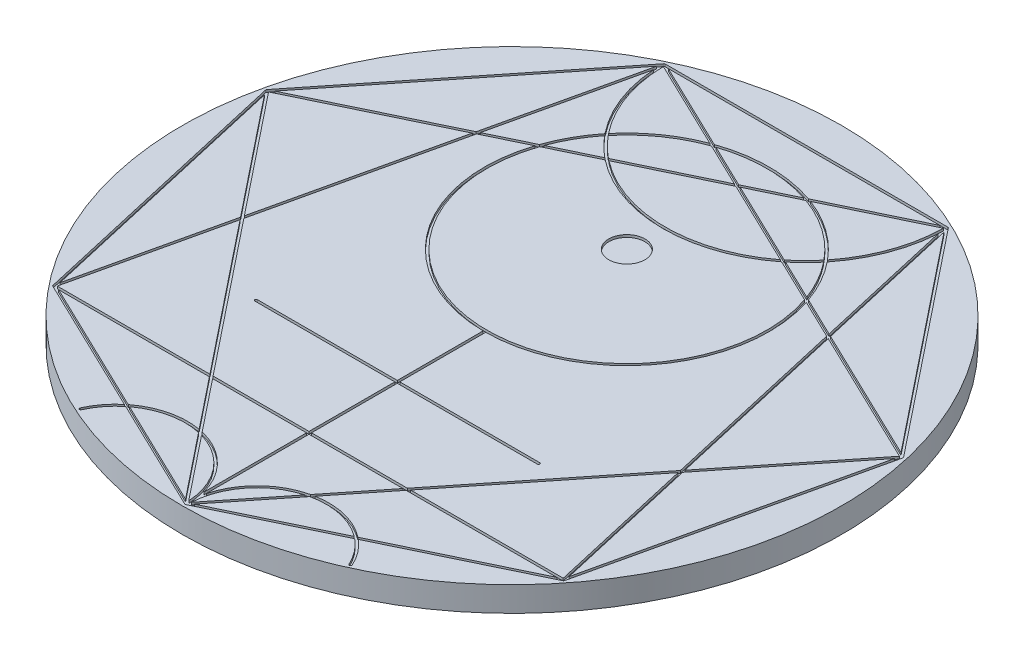
SolidWorks part; units mm, degrees
ref_plane "Front Plane" through (0, 0, 0) normal (0, 0, 1) x (1, 0, 0)
ref_plane "Top Plane" through (0, 0, 0) normal (0, 1, 0) x (1, 0, 0)
ref_plane "Right Plane" through (0, 0, 0) normal (1, 0, 0) x (0, 0, -1)
sketch "Sketch1" plane through (0, 0, 0) normal (0, 1, 0) x (1, 0, 0)
  circle A0 centre (0, 0) radius 132.5
  dimension "D1" = 265
extrude "Boss-Extrude1" add sketch "Sketch1" against normal blind 10
sketch "Sketch2" plane through (0, 0, 0) normal (0, 1, 0) x (1, 0, 0)
  line L0 (-102.3417, -81.6148) -> (102.3417, -81.6148)
  line L1 (102.3417, -81.6148) -> (56.7954, 117.9368)
  line L2 (56.7954, 117.9368) -> (-127.6181, 29.128)
  line L3 (-127.6181, 29.128) -> (0, -130.9)
  line L4 (0, -130.9) -> (127.6181, 29.128)
  line L5 (127.6181, 29.128) -> (-56.7954, 117.9368)
  line L6 (-56.7954, 117.9368) -> (-102.3417, -81.6148)
  line L7 (56.7954, 117.9368) -> (56.7954, 63.2344) construction
  line L8 (0, -130.9) -> (102.3417, -81.6148)
  line L9 (102.3417, -81.6148) -> (127.6181, 29.128)
  line L10 (127.6181, 29.128) -> (56.7954, 117.9368)
  line L11 (56.7954, 117.9368) -> (-56.7954, 117.9368)
  line L12 (-56.7954, 117.9368) -> (-127.6181, 29.128)
  line L13 (-127.6181, 29.128) -> (-102.3417, -81.6148)
  line L14 (-102.3417, -81.6148) -> (0, -130.9)
  line L15 (-56.7954, 117.9368) -> (-56.7954, 63.2344) construction
  line L16 (-56.7954, 90.5856) -> (56.7954, 90.5856) construction
  line L17 (-56.7954, 63.2344) -> (-56.7954, -119.7102) construction
  line L18 (0, -130.9) -> (0, -10.6142)
  line L19 (-35.4113, 73.5324) -> (-35.4113, 107.6388) construction
  line L20 (56.7954, -119.7102) -> (56.7954, 46.1812) construction
  line L21 (-56.7954, -46.1145) -> (56.7954, -46.1145)
  line L22 (56.7954, -10.6142) -> (-56.7954, -10.6142) construction
  line L23 (56.7954, -10.6142) -> (-56.7954, -81.6148) construction
  line L24 (0, -81.6148) -> (-56.7954, -46.1145) construction
  line L25 (56.7954, -81.6148) -> (-56.7954, -10.6142) construction
  line L26 (0, -81.6148) -> (56.7954, -46.1145) construction
  line L27 (56.7954, -46.1145) -> (0, -10.6142) construction
  line L28 (0, -10.6142) -> (-56.7954, -46.1145) construction
  line L29 (35.4113, 107.6388) -> (35.4113, 73.5324) construction
  circle A0 centre (0, 0) radius 130.9
  circle A1 centre (0, 0) radius 117.9368 construction
  circle A3 centre (0, 46.1812) radius 56.7954
  arc A4 (-0.0451, -132.5) -> (-54.8645, -120.6074) centre (-28.3977, -130.9) ccw
  arc A5 (54.8645, -120.6074) -> (0.0451, -132.5) centre (28.3977, -130.9) ccw
  circle A6 centre (0, 0) radius 132.5
  circle A7 centre (0, 0) radius 132.5 construction
  circle A9 centre (0, 46.1812) radius 7.27
  arc A10 (-56.7673, 119.7235) -> (56.7673, 119.7235) centre (0, 117.9368) ccw
  point P7 (35.4113, 90.5856)
  point P31 (0, -130.9)
  point P33 (-35.4113, 90.5856)
  point P40 (0, -46.1145)
  point P50 (-28.3977, -63.8647)
  point P54 (28.3977, -28.3643)
  point P55 (28.3977, -63.8647)
  point P56 (-28.3977, -28.3643)
  point P57 (-35.4113, 90.5856)
  point P58 (0, 0)
  point P59 (0, 0)
  point P60 (35.4113, 90.5856)
  dimension "D1" = 261.8
  dimension "D2" = 14.54
sketch "Sketch4" plane through (0, 0, 0) normal (0, 1, 0) x (1, 0, 0)
  line L4 (0, -130.9) -> (0, -10.6142) construction
  line L11 (-0.5, -123.3637) -> (-0.5, -46.6145)
  line L12 (0.5, -123.3637) -> (0.5, -46.6145)
  line L13 (56.7954, -46.1145) -> (-56.7954, -46.1145) construction
  line L14 (56.7954, -46.6145) -> (0.5, -46.6145)
  line L15 (56.7954, -45.6145) -> (0.5, -45.6145)
  line L16 (-0.5, -46.6145) -> (-56.7954, -46.6145)
  line L17 (-0.5, -45.6145) -> (-0.5, -11.112)
  line L18 (-0.5, -45.6145) -> (-56.7954, -45.6145)
  line L19 (0.5, -45.6145) -> (0.5, -11.112)
  circle A11 centre (0, 46.1812) radius 7.27
  circle A42 centre (0, 0) radius 130.9 construction
  arc A43 (54.8645, -120.6074) -> (0.0451, -132.5) centre (28.3977, -130.9) ccw construction
  arc A44 (54.2425, -119.1325) -> (0, -130.9) centre (28.3977, -130.9) ccw construction
  arc A45 (54.6976, -118.9253) -> (0.5, -123.3637) centre (28.3977, -130.9) ccw
  arc A46 (53.7875, -119.3397) -> (0.5, -130.9) centre (28.3977, -130.9) ccw
  arc A47 (53.7875, -119.3397) -> (54.6976, -118.9253) centre (54.2425, -119.1325) ccw
  arc A48 (-0.5, -130.9) -> (0.5, -130.9) centre (0, -130.9) ccw
  arc A49 (-0.5, -130.9) -> (0.5, -130.9) centre (0, -130.9) ccw
  arc A51 (56.7954, -46.6145) -> (56.7954, -45.6145) centre (56.7954, -46.1145) ccw
  arc A52 (-56.7954, -45.6145) -> (-56.7954, -46.6145) centre (-56.7954, -46.1145) ccw
  arc A53 (-54.2425, -119.1325) -> (0, -130.9) centre (-28.3977, -130.9) cw construction
  arc A54 (-53.7875, -119.3397) -> (-54.6976, -118.9253) centre (-54.2425, -119.1325) cw
  arc A55 (-54.6976, -118.9253) -> (-0.5, -123.3637) centre (-28.3977, -130.9) cw
  arc A56 (-53.7875, -119.3397) -> (-0.5, -130.9) centre (-28.3977, -130.9) cw
  arc A57 (-44.0241, 81.2675) -> (44.0241, 81.2675) centre (0, 46.1812) ccw
  arc A58 (0.5, -11.112) -> (44.6715, 82.059) centre (0, 46.1812) ccw
  arc A59 (56.7954, 117.9368) -> (-56.7954, 117.9368) centre (0, 117.9368) cw construction
  arc A60 (-57.2954, 117.9368) -> (-44.6715, 82.059) centre (0, 117.9368) ccw
  arc A61 (-56.2954, 117.9368) -> (-44.0241, 82.8505) centre (0, 117.9368) ccw
  arc A62 (-56.2954, 117.9368) -> (-57.2954, 117.9368) centre (-56.7954, 117.9368) ccw
  arc A63 (57.2954, 117.9368) -> (56.2954, 117.9368) centre (56.7954, 117.9368) ccw
  arc A64 (-56.7673, 119.7235) -> (56.7673, 119.7235) centre (0, 117.9368) ccw construction
  arc A65 (-44.0241, 81.2675) -> (44.0241, 81.2675) centre (0, 117.9368) ccw
  arc A66 (-44.6715, 82.059) -> (-0.5, -11.112) centre (0, 46.1812) ccw
  arc A67 (-43.3815, 82.059) -> (43.3815, 82.059) centre (0, 117.9368) ccw
  arc A68 (44.6715, 82.059) -> (57.2954, 117.9368) centre (0, 117.9368) ccw
  arc A69 (44.0241, 82.8505) -> (-44.0241, 82.8505) centre (0, 46.1812) ccw
  arc A70 (44.0241, 82.8505) -> (56.2954, 117.9368) centre (0, 117.9368) ccw
  arc A71 (43.3815, 82.059) -> (-43.3815, 82.059) centre (0, 46.1812) ccw
  circle A72 centre (0, 0) radius 132.5
  circle A73 centre (0, 46.1812) radius 56.2954
  point P0 (54.2425, -119.1325)
  point P1 (22.3771, -103.1479)
  point P16 (0, -70.7571)
  point P21 (0, -46.1145)
  point P42 (0, 61.1414)
  dimension "D1" = 1
  dimension "D2" = 1
  dimension "D3" = 1
  dimension "D4" = 1
  dimension "D5" = 1
  dimension "D6" = 14.54
extrude "Cut-Extrude2" cut sketch "Sketch4" against normal blind 1 contours A65 A73 A67 | A70 A69 A61 A62 A60 A66 L17 L18 A52 L16 L11 A55 A54 A56 A48 A46 A47 A45 L12 L14 A51 L15 L19 A58 A68 A63 A73 A57 A71 | A11
sketch "Sketch5" plane through (0, 0, 0) normal (0, 1, 0) x (1, 0, 0)
  line L0 (-102.3417, -81.6148) -> (102.3417, -81.6148) construction
  line L1 (0.2169, -131.3505) -> (102.5587, -82.0653)
  line L2 (102.8292, -81.7261) -> (128.1055, 29.0167)
  line L3 (128.009, 29.4397) -> (57.1863, 118.2486)
  line L4 (56.7954, 118.4368) -> (-56.7954, 118.4368)
  line L5 (-57.1863, 118.2486) -> (-128.009, 29.4397)
  line L6 (-128.1055, 29.0167) -> (-102.8292, -81.7261)
  line L7 (-102.5587, -82.0653) -> (-0.2169, -131.3505)
  line L9 (102.3417, -79.3678) -> (126.6431, 27.1035)
  line L10 (125.8613, 30.529) -> (57.7703, 115.9124)
  line L11 (54.6047, 117.4368) -> (-54.6047, 117.4368)
  line L15 (-101.7148, -81.1148) -> (-40.3419, -81.1148)
  line L16 (-100.1511, -82.1148) -> (-39.5444, -82.1148)
  line L17 (102.3417, -81.6148) -> (56.7954, 117.9368) construction
  line L19 (102.3417, -79.3678) -> (88.8555, -20.2807)
  line L20 (56.7954, 117.9368) -> (-127.6181, 29.128) construction
  line L22 (54.6047, 117.4368) -> (0, 91.1406)
  line L23 (-127.6181, 29.128) -> (0, -130.9) construction
  line L25 (-126.6431, 27.1035) -> (-88.8555, -20.2807)
  line L26 (0, -130.9) -> (127.6181, 29.128) construction
  line L28 (1.7568, -129.499) -> (39.5444, -82.1148)
  line L29 (127.6181, 29.128) -> (-56.7954, 117.9368) construction
  line L31 (125.8613, 30.529) -> (71.2566, 56.8252)
  line L32 (-102.3417, -81.6148) -> (-56.7954, 117.9368) construction
  line L33 (-102.3417, -79.3678) -> (-88.8555, -20.2807)
  line L36 (-57.7703, 115.9124) -> (-125.8613, 30.529)
  line L37 (-56.7047, 117.2486) -> (-57.0518, 116.8133) [skipped]
  line L38 (56.4474, 117.2143) -> (1.1524, 90.5856)
  line L39 (126.8362, 28.9495) -> (71.5412, 55.5782)
  line L40 (1.7568, -129.499) -> (100.1511, -82.1148)
  line L41 (101.7148, -81.1148) -> (88.058, -21.2807)
  line L42 (0.2169, -130.2406) -> (0.7185, -129.999) [skipped]
  line L43 (0, -130.0981) -> (38.2654, -82.1148)
  line L44 (-101.7148, -81.1148) -> (-88.058, -21.2807)
  line L45 (-100.1511, -82.1148) -> (-1.7568, -129.499)
  line L46 (-101.6909, -81.3733) -> (-101.1894, -81.6148) [skipped]
  line L47 (-126.6431, 27.1035) -> (-102.3417, -79.3678)
  line L48 (-127.0234, 28.7698) -> (-126.8996, 28.227) [skipped]
  line L49 (-126.8362, 28.9495) -> (-88.5709, -19.0337)
  line L50 (88.8555, -20.2807) -> (126.6431, 27.1035)
  line L51 (87.7734, -20.0337) -> (70.3888, 56.1332)
  line L52 (88.5709, -19.0337) -> (126.8362, 28.9495)
  line L53 (88.5709, -19.0337) -> (71.5412, 55.5782)
  line L54 (40.3419, -81.1148) -> (88.058, -21.2807)
  line L55 (39.5444, -82.1148) -> (100.1511, -82.1148)
  line L56 (39.0628, -81.1148) -> (87.7734, -20.0337)
  line L57 (40.3419, -81.1148) -> (101.7148, -81.1148)
  line L58 (-38.2654, -82.1148) -> (38.2654, -82.1148)
  line L59 (-39.5444, -82.1148) -> (-1.7568, -129.499)
  line L60 (-39.0628, -81.1148) -> (39.0628, -81.1148)
  line L61 (-38.2654, -82.1148) -> (0, -130.0981)
  line L62 (-87.7734, -20.0337) -> (-70.3888, 56.1332)
  line L63 (-88.058, -21.2807) -> (-40.3419, -81.1148)
  line L64 (-87.7734, -20.0337) -> (-39.0628, -81.1148)
  line L65 (-88.5709, -19.0337) -> (-71.5412, 55.5782)
  line L66 (-71.5412, 55.5782) -> (-126.8362, 28.9495)
  line L67 (-70.1042, 57.3802) -> (-56.4474, 117.2143)
  line L68 (-71.2566, 56.8252) -> (-125.8613, 30.529)
  line L69 (-71.2566, 56.8252) -> (-57.7703, 115.9124)
  line L70 (0, 90.0307) -> (-70.3888, 56.1332)
  line L71 (0, 91.1406) -> (-54.6047, 117.4368)
  line L72 (-1.1524, 90.5856) -> (-70.1042, 57.3802)
  line L73 (-1.1524, 90.5856) -> (-56.4474, 117.2143)
  line L74 (70.3888, 56.1332) -> (0, 90.0307)
  line L75 (71.2566, 56.8252) -> (57.7703, 115.9124)
  line L76 (70.1042, 57.3802) -> (1.1524, 90.5856)
  line L77 (70.1042, 57.3802) -> (56.4474, 117.2143)
  circle A0 centre (0, 0) radius 132.5
  circle A2 centre (0, 0) radius 117.4368 construction
  arc A3 (-102.8292, -81.7261) -> (-102.5587, -82.0653) centre (-102.3417, -81.6148) ccw
  arc A5 (-128.009, 29.4397) -> (-128.1055, 29.0167) centre (-127.6181, 29.128) ccw
  arc A8 (-57.1863, 118.2486) -> (-56.7954, 118.4368) centre (-56.7954, 117.9368) cw
  arc A9 (56.7954, 118.4368) -> (57.1863, 118.2486) centre (56.7954, 117.9368) cw
  arc A12 (128.1055, 29.0167) -> (128.009, 29.4397) centre (127.6181, 29.128) ccw
  arc A13 (102.8292, -81.7261) -> (102.5587, -82.0653) centre (102.3417, -81.6148) cw
  arc A16 (-0.2169, -131.3505) -> (0.2169, -131.3505) centre (0, -130.9) ccw
  arc A18 (102.5587, -82.0653) -> (102.8292, -81.7261) centre (102.3417, -81.6148) ccw
  arc A20 (57.1863, 118.2486) -> (56.7954, 118.4368) centre (56.7954, 117.9368) ccw
  arc A21 (57.1863, 118.2486) -> (56.7954, 118.4368) centre (56.7954, 117.9368) ccw
  arc A22 (-128.009, 29.4397) -> (-128.1055, 29.0167) centre (-127.6181, 29.128) ccw
  arc A23 (-128.009, 29.4397) -> (-128.1055, 29.0167) centre (-127.6181, 29.128) ccw
  arc A24 (-0.2169, -131.3505) -> (0.2169, -131.3505) centre (0, -130.9) ccw
  arc A25 (-0.2169, -131.3505) -> (0.2169, -131.3505) centre (0, -130.9) ccw
  arc A26 (128.1055, 29.0167) -> (128.009, 29.4397) centre (127.6181, 29.128) ccw
  arc A27 (128.1055, 29.0167) -> (128.009, 29.4397) centre (127.6181, 29.128) ccw
  arc A28 (-56.7954, 118.4368) -> (-57.1863, 118.2486) centre (-56.7954, 117.9368) ccw
  arc A29 (-56.2954, 117.9368) -> (-57.2954, 117.9368) centre (-56.7954, 117.9368) ccw construction
  arc A30 (-102.8292, -81.7261) -> (-102.5587, -82.0653) centre (-102.3417, -81.6148) ccw
  arc A31 (-56.7954, 118.4368) -> (-57.1863, 118.2486) centre (-56.7954, 117.9368) ccw
  arc A32 (102.5587, -82.0653) -> (102.8292, -81.7261) centre (102.3417, -81.6148) ccw
  arc A33 (-102.8292, -81.7261) -> (-102.5587, -82.0653) centre (-102.3417, -81.6148) ccw
  point P45 (0, -130.345)
  point P52 (0, -81.6148)
  point P57 (79.5686, 18.161)
  point P65 (-35.4113, 73.5324)
  point P73 (-63.809, -50.886)
  point P81 (63.809, -50.886)
  point P89 (35.4113, 73.5324)
  point P100 (-79.5686, 18.161)
  arc M31 (-44.0241, 82.8505) -> (44.0241, 82.8505) centre (0, 46.1812) cw
  arc M32 (44.0241, 82.8505) -> (56.2954, 117.9368) centre (0, 117.9368) ccw
  arc M33 (56.2954, 117.9368) -> (57.2954, 117.9368) centre (56.7954, 117.9368) cw
  arc M34 (57.2954, 117.9368) -> (44.6715, 82.059) centre (0, 117.9368) cw
  arc M35 (44.6715, 82.059) -> (0.5, -11.112) centre (0, 46.1812) cw
  line M40 (0.5, -46.6145) -> (0.5, -123.3637)
  arc M41 (0.5, -123.3637) -> (54.6976, -118.9253) centre (28.3977, -130.9) cw
  arc M43 (53.7875, -119.3397) -> (0.5, -130.9) centre (28.3977, -130.9) ccw
  arc M44 (0.5, -130.9) -> (-0.5, -130.9) centre (0, -130.9) cw
  arc M45 (-0.5, -130.9) -> (-53.7875, -119.3397) centre (-28.3977, -130.9) ccw
  arc M47 (-54.6976, -118.9253) -> (-0.5, -123.3637) centre (-28.3977, -130.9) cw
  line M48 (-0.5, -123.3637) -> (-0.5, -46.6145)
  arc M53 (-0.5, -11.112) -> (-44.6715, 82.059) centre (0, 46.1812) cw
  arc M54 (-44.6715, 82.059) -> (-57.2954, 117.9368) centre (0, 117.9368) cw
  arc M55 (-57.2954, 117.9368) -> (-56.2954, 117.9368) centre (-56.7954, 117.9368) cw
  arc M56 (-56.2954, 117.9368) -> (-44.0241, 82.8505) centre (0, 117.9368) ccw
  dimension "D2" = 0.5
  dimension "D1" = 1
extrude "Cut-Extrude3" cut sketch "Sketch5" against normal blind 1 contours A13 L2 A12 L3 L77 L76 L74 L51 L56 L60 L58 L43 L28 L55 L40 L1 L57 L54 L41 L19 L50 L9 L52 L53 L39 L31 L75 L10 M33 M34 M35 M40 M41 | L43 L1 L40 L28 M43 M44 | L61 L59 L45 L7 M45 M44 | L5 A5 L6 A3 L7 L45 L16 L59 L61 L58 L60 L64 L62 L70 L72 L67 L44 L63 L15 L47 L25 L33 L66 L65 L49 L69 L68 L36 M47 M48 M53 M54 M55 | L76 L38 L22 L71 L73 L72 L70 L74 M35 M31 M53 | L73 L71 L11 L22 L38 L4 M31 M32 M33 M55 M56
